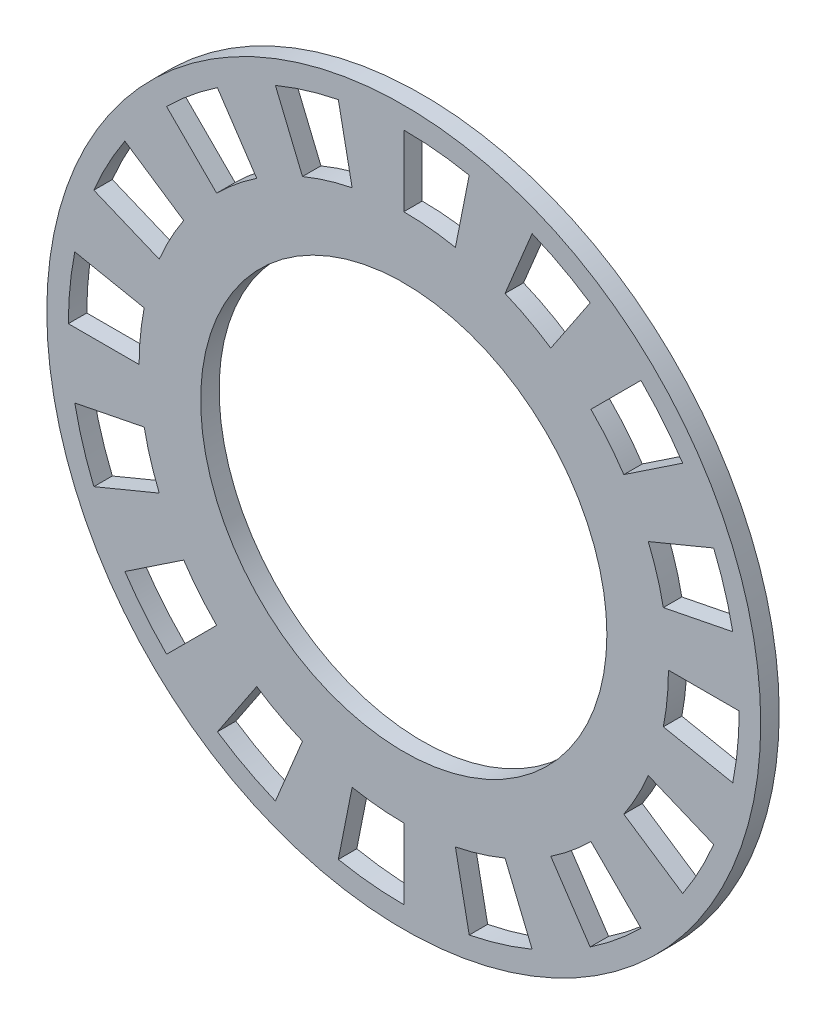
SolidWorks part; units mm, degrees
ref_plane "Alzado" through (0, 0, 0) normal (0, 0, 1) x (1, 0, 0)
ref_plane "Planta" through (0, 0, 0) normal (0, 1, 0) x (1, 0, 0)
ref_plane "Vista lateral" through (0, 0, 0) normal (1, 0, 0) x (0, 0, -1)
sketch "Model" plane through (0, 0, 0) normal (0, 0, 1) x (1, 0, 0)
  line L0 (38.4904, 287.0178) -> (38.4904, 292.7678)
  line L1 (34.296, 286.6047) -> (33.1742, 292.2442)
  line L2 (30.2627, 285.3812) -> (28.0623, 290.6935)
  line L3 (26.5456, 283.3944) -> (23.3511, 288.1753)
  line L4 (23.2876, 280.7206) -> (19.2217, 284.7864)
  line L5 (20.6138, 277.4625) -> (15.8328, 280.6571)
  line L6 (18.627, 273.7455) -> (13.3147, 275.9459)
  line L7 (17.4035, 269.7122) -> (11.764, 270.834)
  line L8 (16.9904, 265.5178) -> (11.2404, 265.5178)
  line L9 (17.4035, 261.3233) -> (11.764, 260.2016)
  line L10 (18.627, 257.2901) -> (13.3147, 255.0897)
  line L11 (20.6138, 253.573) -> (15.8328, 250.3785)
  line L12 (23.2876, 250.315) -> (19.2217, 246.2491)
  line L13 (26.5456, 247.6412) -> (23.3511, 242.8602)
  line L14 (30.2627, 245.6544) -> (28.0623, 240.3421)
  line L15 (34.296, 244.4309) -> (33.1742, 238.7914)
  line L16 (38.4904, 244.0178) -> (38.4904, 238.2678)
  line L17 (42.6848, 244.4309) -> (43.8066, 238.7914)
  line L18 (46.7181, 245.6544) -> (48.9185, 240.3421)
  line L19 (50.4352, 247.6412) -> (53.6297, 242.8602)
  line L20 (53.6932, 250.315) -> (57.7591, 246.2491)
  line L21 (56.367, 253.573) -> (61.1479, 250.3785)
  line L22 (58.3538, 257.2901) -> (63.6661, 255.0897)
  line L23 (59.5773, 261.3233) -> (65.2168, 260.2016)
  line L24 (59.9904, 265.5178) -> (65.7404, 265.5178)
  line L25 (59.5773, 269.7122) -> (65.2168, 270.834)
  line L26 (58.3538, 273.7455) -> (63.6661, 275.9459)
  line L27 (56.367, 277.4625) -> (61.1479, 280.6571)
  line L28 (53.6932, 280.7206) -> (57.7591, 284.7864)
  line L29 (50.4352, 283.3944) -> (53.6297, 288.1753)
  line L30 (46.7181, 285.3812) -> (48.9185, 290.6935)
  line L31 (42.6848, 286.6047) -> (43.8066, 292.2442)
  circle A0 centre (38.4904, 265.5178) radius 29
  arc A1 (50.4352, 283.3944) -> (46.7181, 285.3812) centre (38.4904, 265.5178) ccw
  arc A2 (53.6297, 288.1753) -> (48.9185, 290.6935) centre (38.4904, 265.5178) ccw
  arc A3 (34.296, 286.6047) -> (30.2627, 285.3812) centre (38.4904, 265.5178) ccw
  arc A4 (33.1742, 292.2442) -> (28.0623, 290.6935) centre (38.4904, 265.5178) ccw
  arc A5 (26.5456, 283.3944) -> (23.2876, 280.7206) centre (38.4904, 265.5178) ccw
  arc A6 (23.3511, 288.1753) -> (19.2217, 284.7864) centre (38.4904, 265.5178) ccw
  arc A7 (15.8328, 280.6571) -> (13.3147, 275.9459) centre (38.4904, 265.5178) ccw
  arc A8 (20.6138, 277.4625) -> (18.627, 273.7455) centre (38.4904, 265.5178) ccw
  arc A9 (17.4035, 269.7122) -> (16.9904, 265.5178) centre (38.4904, 265.5178) ccw
  arc A10 (11.764, 270.834) -> (11.2404, 265.5178) centre (38.4904, 265.5178) ccw
  arc A11 (17.4035, 261.3233) -> (18.627, 257.2901) centre (38.4904, 265.5178) ccw
  arc A12 (11.764, 260.2016) -> (13.3147, 255.0897) centre (38.4904, 265.5178) ccw
  arc A13 (20.6138, 253.573) -> (23.2876, 250.315) centre (38.4904, 265.5178) ccw
  arc A14 (15.8328, 250.3785) -> (19.2217, 246.2491) centre (38.4904, 265.5178) ccw
  arc A15 (26.5456, 247.6412) -> (30.2627, 245.6544) centre (38.4904, 265.5178) ccw
  arc A16 (23.3511, 242.8602) -> (28.0623, 240.3421) centre (38.4904, 265.5178) ccw
  arc A17 (33.1742, 238.7914) -> (38.4904, 238.2678) centre (38.4904, 265.5178) ccw
  arc A18 (34.296, 244.4309) -> (38.4904, 244.0178) centre (38.4904, 265.5178) ccw
  arc A19 (42.6848, 244.4309) -> (46.7181, 245.6544) centre (38.4904, 265.5178) ccw
  arc A20 (43.8066, 238.7914) -> (48.9185, 240.3421) centre (38.4904, 265.5178) ccw
  arc A21 (53.6297, 242.8602) -> (57.7591, 246.2491) centre (38.4904, 265.5178) ccw
  arc A22 (50.4352, 247.6412) -> (53.6932, 250.315) centre (38.4904, 265.5178) ccw
  arc A23 (56.367, 253.573) -> (58.3538, 257.2901) centre (38.4904, 265.5178) ccw
  arc A24 (61.1479, 250.3785) -> (63.6661, 255.0897) centre (38.4904, 265.5178) ccw
  arc A25 (65.2168, 260.2016) -> (65.7404, 265.5178) centre (38.4904, 265.5178) ccw
  arc A26 (59.5773, 261.3233) -> (59.9904, 265.5178) centre (38.4904, 265.5178) ccw
  arc A27 (59.5773, 269.7122) -> (58.3538, 273.7455) centre (38.4904, 265.5178) ccw
  arc A28 (65.2168, 270.834) -> (63.6661, 275.9459) centre (38.4904, 265.5178) ccw
  arc A29 (61.1479, 280.6571) -> (57.7591, 284.7864) centre (38.4904, 265.5178) ccw
  arc A30 (56.367, 277.4625) -> (53.6932, 280.7206) centre (38.4904, 265.5178) ccw
  arc A31 (42.6848, 286.6047) -> (38.4904, 287.0178) centre (38.4904, 265.5178) ccw
  arc A32 (43.8066, 292.2442) -> (38.4904, 292.7678) centre (38.4904, 265.5178) ccw
  circle A33 centre (38.4904, 265.5178) radius 16.5
extrude "Saliente-Extruir1" add sketch "Model" along normal blind 1.5
